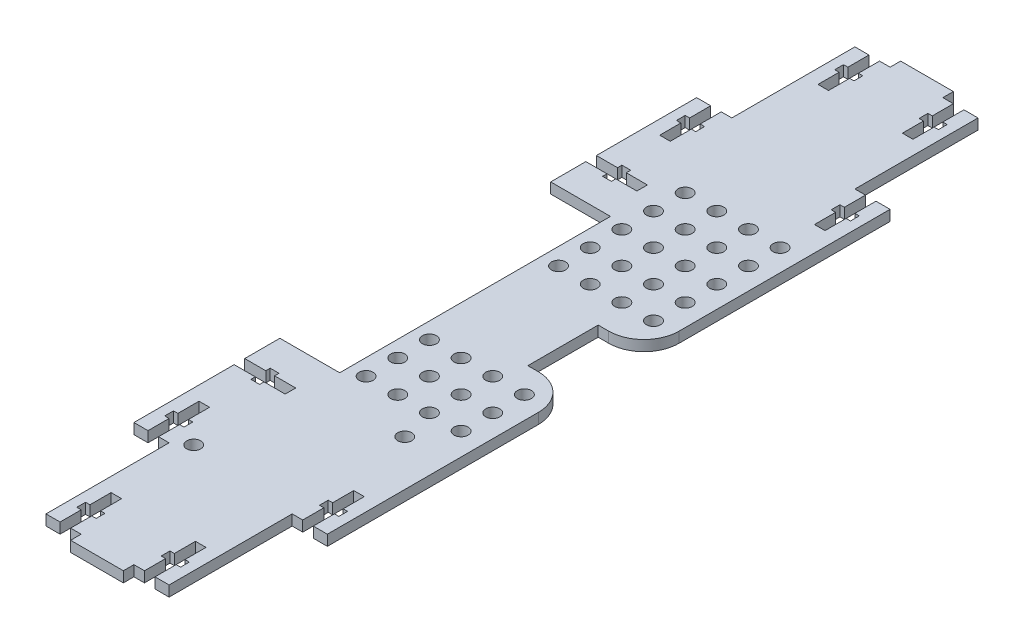
SolidWorks part; units mm, degrees
ref_plane "Спереди" through (0, 0, 0) normal (0, 0, 1) x (1, 0, 0)
ref_plane "Сверху" through (0, 0, 0) normal (0, 1, 0) x (1, 0, 0)
ref_plane "Справа" through (0, 0, 0) normal (1, 0, 0) x (0, 0, -1)
sketch "Эскиз1" plane through (0, 0, 0) normal (0, 1, 0) x (1, 0, 0)
  line L1 (-27.5, -80) -> (27.5, -80)
  line L2 (-27.5, -80) -> (-27.5, 80)
  line L3 (-27.5, 80) -> (27.5, 80)
  line L4 (27.5, -80) -> (27.5, 80)
  line L5 (-27.5, -80) -> (27.5, 80) construction
  line L6 (-27.5, 80) -> (27.5, -80) construction
  point P0 (0, 0)
  dimension "D1" = 55
  dimension "D2" = 160
extrude "Бобышка-Вытянуть1" add sketch "Эскиз1" along normal blind 3
sketch "Эскиз2" plane through (0, 0, -80) normal (0, 0, -1) x (-1, 0, 0)
  line L0 (-27.5, 0) -> (27.5, 0) construction
  line L1 (-17.5, 0) -> (17.5, 0)
  line L2 (-17.5, 0) -> (-17.5, 3)
  line L3 (-17.5, 3) -> (17.5, 3)
  line L4 (17.5, 0) -> (17.5, 3)
  line L5 (-27.5, 3) -> (27.5, 3) construction
  point P8 (0, 3)
  dimension "D1" = 35
  dimension "D2" = 27.5
extrude "Бобышка-Вытянуть2" add sketch "Эскиз2" along normal blind 35 and the other way blind 195
sketch "Эскиз3" plane through (0, 0, -115) normal (0, 0, -1) x (-1, 0, 0)
  line L0 (-17.5, 0) -> (17.5, 0) construction
  line L1 (-7.5, 0) -> (7.5, 0)
  line L2 (-7.5, 0) -> (-7.5, 3)
  line L3 (-7.5, 3) -> (7.5, 3)
  line L4 (7.5, 0) -> (7.5, 3)
  line L5 (17.5, 3) -> (-17.5, 3) construction
  point P8 (0, 0)
  dimension "D1" = 15
  dimension "D2" = 27.5
extrude "Бобышка-Вытянуть3" add sketch "Эскиз3" along normal blind 3 and the other way blind 233
sketch "Эскиз4" plane through (0, 3, 0) normal (0, 1, 0) x (1, 0, 0)
  line L0 (-23.5, 80) -> (-23.5, 74)
  line L1 (-13.5, 115) -> (-13.5, 109)
  line L2 (-23.5, 74) -> (-24.75, 74)
  line L3 (-24.75, 74) -> (-24.75, 71.5)
  line L4 (-24.75, 71.5) -> (-23.5, 71.5)
  line L5 (-23.5, 71.5) -> (-23.5, 65.5)
  line L6 (-23.5, 65.5) -> (-20.5, 65.5)
  line L7 (-20.5, 65.5) -> (-20.5, 71.5)
  line L8 (-20.5, 71.5) -> (-19.25, 71.5)
  line L9 (-19.25, 71.5) -> (-19.25, 74)
  line L10 (-19.25, 74) -> (-20.5, 74)
  line L11 (-20.5, 74) -> (-20.5, 80)
  line L12 (-13.5, 109) -> (-14.75, 109)
  line L13 (-20.5, 80) -> (-23.5, 80)
  line L14 (-14.75, 109) -> (-14.75, 106.5)
  line L15 (-14.75, 106.5) -> (-13.5, 106.5)
  line L16 (-13.5, 106.5) -> (-13.5, 100.5)
  line L17 (-13.5, 100.5) -> (-10.5, 100.5)
  line L18 (-10.5, 100.5) -> (-10.5, 106.5)
  line L19 (-10.5, 106.5) -> (-9.25, 106.5)
  line L20 (-9.25, 106.5) -> (-9.25, 109)
  line L21 (-9.25, 109) -> (-10.5, 109)
  line L22 (-10.5, 109) -> (-10.5, 115)
  line L23 (-10.5, 115) -> (-13.5, 115)
  line L24 (-17.5, 80) -> (-27.5, 80) construction
  line L25 (-17.5, 115) -> (-7.5, 115) construction
  line L26 (0, 118) -> (0, 75.6534) construction
  line L27 (-7.5, 118) -> (7.5, 118) construction
  line L28 (-27.5, 0) -> (22.9967, 0) construction
  line L29 (-27.5, 80) -> (-27.5, -80) construction
  line L30 (10.5, 115) -> (13.5, 115)
  line L31 (10.5, 109) -> (10.5, 115)
  line L32 (9.25, 109) -> (10.5, 109)
  line L33 (9.25, 106.5) -> (9.25, 109)
  line L34 (10.5, 106.5) -> (9.25, 106.5)
  line L35 (10.5, 100.5) -> (10.5, 106.5)
  line L36 (13.5, 100.5) -> (10.5, 100.5)
  line L37 (13.5, 106.5) -> (13.5, 100.5)
  line L38 (14.75, 106.5) -> (13.5, 106.5)
  line L39 (14.75, 109) -> (14.75, 106.5)
  line L40 (20.5, 80) -> (23.5, 80)
  line L41 (13.5, 109) -> (14.75, 109)
  line L42 (20.5, 74) -> (20.5, 80)
  line L43 (19.25, 74) -> (20.5, 74)
  line L44 (19.25, 71.5) -> (19.25, 74)
  line L45 (20.5, 71.5) -> (19.25, 71.5)
  line L46 (20.5, 65.5) -> (20.5, 71.5)
  line L47 (23.5, 65.5) -> (20.5, 65.5)
  line L48 (23.5, 71.5) -> (23.5, 65.5)
  line L49 (24.75, 71.5) -> (23.5, 71.5)
  line L50 (24.75, 74) -> (24.75, 71.5)
  line L51 (23.5, 74) -> (24.75, 74)
  line L52 (13.5, 115) -> (13.5, 109)
  line L53 (23.5, 80) -> (23.5, 74)
  line L54 (-10.5, -115) -> (-13.5, -115)
  line L55 (-10.5, -109) -> (-10.5, -115)
  line L56 (-9.25, -109) -> (-10.5, -109)
  line L57 (-9.25, -106.5) -> (-9.25, -109)
  line L58 (-10.5, -106.5) -> (-9.25, -106.5)
  line L59 (-10.5, -100.5) -> (-10.5, -106.5)
  line L60 (-13.5, -100.5) -> (-10.5, -100.5)
  line L61 (-13.5, -106.5) -> (-13.5, -100.5)
  line L62 (-14.75, -106.5) -> (-13.5, -106.5)
  line L63 (-14.75, -109) -> (-14.75, -106.5)
  line L64 (-13.5, -109) -> (-14.75, -109)
  line L65 (-13.5, -115) -> (-13.5, -109)
  line L66 (13.5, -115) -> (13.5, -109)
  line L67 (13.5, -109) -> (14.75, -109)
  line L68 (14.75, -109) -> (14.75, -106.5)
  line L69 (14.75, -106.5) -> (13.5, -106.5)
  line L70 (13.5, -106.5) -> (13.5, -100.5)
  line L71 (13.5, -100.5) -> (10.5, -100.5)
  line L72 (10.5, -100.5) -> (10.5, -106.5)
  line L73 (10.5, -106.5) -> (9.25, -106.5)
  line L74 (9.25, -106.5) -> (9.25, -109)
  line L75 (9.25, -109) -> (10.5, -109)
  line L76 (10.5, -109) -> (10.5, -115)
  line L77 (10.5, -115) -> (13.5, -115)
  line L78 (-20.5, -80) -> (-23.5, -80)
  line L79 (-20.5, -74) -> (-20.5, -80)
  line L80 (-19.25, -74) -> (-20.5, -74)
  line L81 (-19.25, -71.5) -> (-19.25, -74)
  line L82 (-20.5, -71.5) -> (-19.25, -71.5)
  line L83 (-20.5, -65.5) -> (-20.5, -71.5)
  line L84 (-23.5, -65.5) -> (-20.5, -65.5)
  line L85 (-23.5, -71.5) -> (-23.5, -65.5)
  line L86 (-24.75, -71.5) -> (-23.5, -71.5)
  line L87 (-24.75, -74) -> (-24.75, -71.5)
  line L88 (-23.5, -74) -> (-24.75, -74)
  line L89 (-23.5, -80) -> (-23.5, -74)
  line L90 (23.5, -80) -> (23.5, -74)
  line L91 (23.5, -74) -> (24.75, -74)
  line L92 (24.75, -74) -> (24.75, -71.5)
  line L93 (24.75, -71.5) -> (23.5, -71.5)
  line L94 (23.5, -71.5) -> (23.5, -65.5)
  line L95 (23.5, -65.5) -> (20.5, -65.5)
  line L96 (20.5, -65.5) -> (20.5, -71.5)
  line L97 (20.5, -71.5) -> (19.25, -71.5)
  line L98 (19.25, -71.5) -> (19.25, -74)
  line L99 (19.25, -74) -> (20.5, -74)
  line L100 (20.5, -74) -> (20.5, -80)
  line L101 (20.5, -80) -> (23.5, -80)
  point P29 (-22, 80)
  point P112 (-12, 115)
  dimension "D1" = 3
  dimension "D2" = 5.5
  dimension "D3" = 6
  dimension "D4" = 2.5
  dimension "D5" = 3
  dimension "D6" = 5.5
  dimension "D7" = 6
  dimension "D8" = 2.5
  dimension "D9" = 4.5
  dimension "D10" = 4
  dimension "D11" = 4.5
extrude "Вырез-Вытянуть1" cut sketch "Эскиз4" against normal blind 3
sketch "Эскиз5" plane through (0, 3, 0) normal (0, 1, 0) x (1, 0, 0)
  line L0 (-27.5, 51.5) -> (-21.5, 51.5)
  line L1 (-21.5, 51.5) -> (-21.5, 52.75)
  line L2 (-21.5, 52.75) -> (-19, 52.75)
  line L3 (-19, 52.75) -> (-19, 51.5)
  line L4 (-19, 51.5) -> (-13, 51.5)
  line L5 (-13, 51.5) -> (-13, 48.5)
  line L6 (-13, 48.5) -> (-19, 48.5)
  line L7 (-19, 48.5) -> (-19, 47.25)
  line L8 (-19, 47.25) -> (-21.5, 47.25)
  line L9 (-21.5, 47.25) -> (-21.5, 48.5)
  line L10 (-21.5, 48.5) -> (-27.5, 48.5)
  line L11 (-27.5, 48.5) -> (-27.5, 51.5)
  line L12 (-27.5, 80) -> (-27.5, -80) construction
  line L13 (-27.5, 0) -> (-6.9327, 0) construction
  line L14 (-27.5, -48.5) -> (-27.5, -51.5)
  line L15 (-21.5, -48.5) -> (-27.5, -48.5)
  line L16 (-21.5, -47.25) -> (-21.5, -48.5)
  line L17 (-19, -47.25) -> (-21.5, -47.25)
  line L18 (-19, -48.5) -> (-19, -47.25)
  line L19 (-13, -48.5) -> (-19, -48.5)
  line L20 (-13, -51.5) -> (-13, -48.5)
  line L21 (-19, -51.5) -> (-13, -51.5)
  line L22 (-19, -52.75) -> (-19, -51.5)
  line L23 (-21.5, -52.75) -> (-19, -52.75)
  line L24 (-21.5, -51.5) -> (-21.5, -52.75)
  line L25 (-27.5, -51.5) -> (-21.5, -51.5)
  point P30 (-27.5, 50)
  dimension "D1" = 3
  dimension "D2" = 6
  dimension "D3" = 2.5
  dimension "D4" = 5.5
  dimension "D5" = 50
extrude "Вырез-Вытянуть2" cut sketch "Эскиз5" against normal blind 3
sketch "Эскиз6" plane through (-27.5, 0, 0) normal (-1, 0, 0) x (0, 0, 1)
  line L0 (-48.5, 3) -> (48.5, 3) construction
  line L1 (-38.5, 3) -> (38.5, 3)
  line L2 (-38.5, 3) -> (-38.5, 0)
  line L3 (-38.5, 0) -> (38.5, 0)
  line L4 (38.5, 3) -> (38.5, 0)
  line L5 (-48.5, 0) -> (48.5, 0) construction
  point P8 (0, 0)
  dimension "D1" = 77
extrude "Вырез-Вытянуть3" cut sketch "Эскиз6" against normal blind 17
sketch "Эскиз8" plane through (0, 3, 0) normal (0, 1, 0) x (1, 0, 0)
  circle A0 centre (-13.5, -77) radius 2
  circle A1 centre (14.5, -45) radius 2
  dimension "D1" = 4
  dimension "D2" = 3
  dimension "D3" = 4
  dimension "D4" = 28
  dimension "D5" = 32
extrude "Вырез-Вытянуть4" cut sketch "Эскиз8" against normal blind 3
sketch "Эскиз9" plane through (0, 3, 0) normal (0, 1, 0) x (1, 0, 0)
  line L0 (27.5, -80) -> (27.5, 80) construction
  line L1 (27.5, -10) -> (14.5, -10)
  line L2 (27.5, -10) -> (27.5, 10)
  line L3 (27.5, 10) -> (14.5, 10)
  line L4 (14.5, -10) -> (14.5, 10)
  line L5 (-10.5, -38.5) -> (-10.5, 38.5) construction
  point P8 (27.5, 0)
  point P9 (27.5, 0)
  dimension "D1" = 20
  dimension "D2" = 25
extrude "Вырез-Вытянуть5" cut sketch "Эскиз9" against normal blind 3
fillet "Скругление1" radius 10 2 edges at (27.5, 1.5, 10) (27.5, 1.5, -10)
sketch "Эскиз10" plane through (0, 3, 0) normal (0, 1, 0) x (1, 0, 0)
  circle A0 centre (21.1273, -35.6021) radius 2
  point P2 (21.1273, -35.6021)
  dimension "D1" = 4
extrude "Вырез-Вытянуть6" cut sketch "Эскиз10" against normal blind 10
pattern_linear "Линейный массив1" count 4 spacing 9 along (-1, 0, 0) count 3 spacing 9 along (0, 0, -1) of "Вырез-Вытянуть6"
sketch "Эскиз11" plane through (0, 3, 0) normal (0, 1, 0) x (1, 0, 0)
  circle A0 centre (21.3113, 18.9196) radius 2
  point P2 (0, 0)
  point P3 (21.3113, 18.9196)
  dimension "D1" = 4
extrude "Вырез-Вытянуть7" cut sketch "Эскиз11" against normal blind 10
pattern_linear "Линейный массив2" count 5 spacing 9 along (0, 0, -1) count 4 spacing 9 along (-1, 0, 0) of "Вырез-Вытянуть7"
